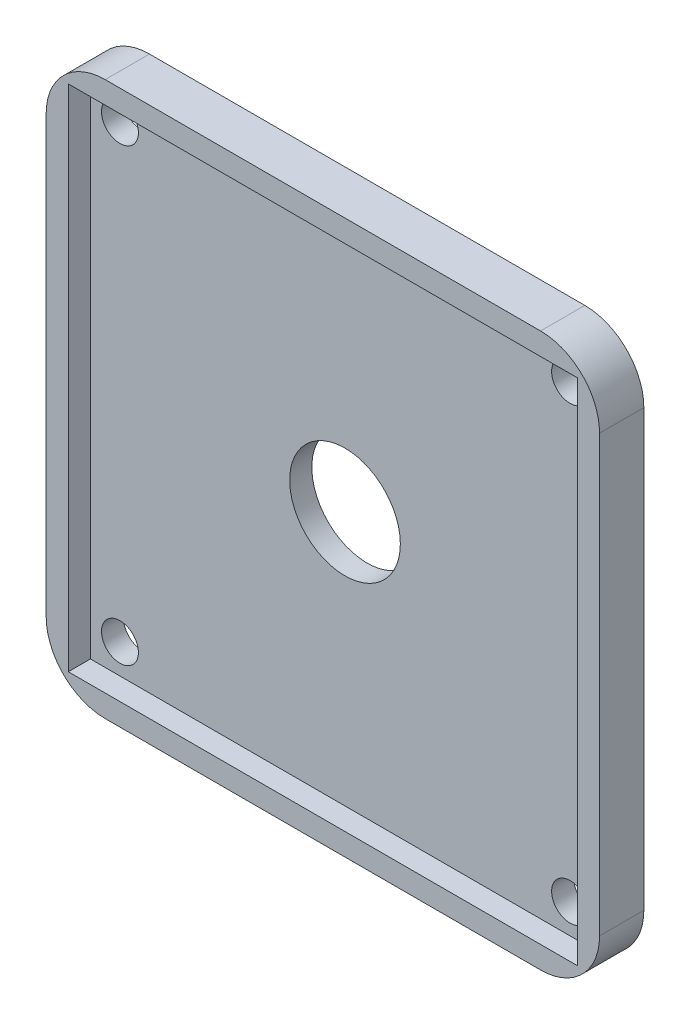
SolidWorks part; units mm, degrees
ref_plane "Front Plane" through (0, 0, 0) normal (0, 0, 1) x (1, 0, 0)
ref_plane "Top Plane" through (0, 0, 0) normal (0, 1, 0) x (1, 0, 0)
ref_plane "Right Plane" through (0, 0, 0) normal (1, 0, 0) x (0, 0, -1)
sketch "Sketch1" plane through (0, 0, 0) normal (0, 0, 1) x (1, 0, 0)
  line L0 (37.5, 75) -> (37.5, 0) construction
  line L1 (0, 0) -> (75, 0)
  line L2 (0, 0) -> (0, 75)
  line L3 (0, 75) -> (75, 75)
  line L4 (75, 0) -> (75, 75)
  line L5 (0, 37.5) -> (75, 37.5) construction
  line L6 (7, 75) -> (7, 68) construction
  line L7 (7, 68) -> (0, 68) construction
  circle A0 centre (7, 68) radius 2.5
  circle A1 centre (68, 68) radius 2.5
  circle A2 centre (68, 7) radius 2.5
  circle A3 centre (7, 7) radius 2.5
  circle A4 centre (37.5, 37.5) radius 7.5
  dimension "D2" = 5
  dimension "D4" = 15
  dimension "D1" = 75
  dimension "D3" = 7
extrude "Boss-Extrude1" add sketch "Sketch1" along normal blind 6
sketch "Sketch2" plane through (0, 0, 6) normal (0, 0, 1) x (1, 0, 0)
  line L0 (72, 3) -> (75, 3) construction
  line L1 (3, 72) -> (72, 72)
  line L2 (3, 72) -> (3, 3)
  line L3 (3, 3) -> (72, 3)
  line L4 (72, 72) -> (72, 3)
  line L5 (75, 0) -> (75, 75) construction
  line L6 (72, 3) -> (72, 0) construction
  line L7 (0, 0) -> (75, 0) construction
  line L8 (3, 72) -> (3, 75) construction
  line L9 (75, 75) -> (0, 75) construction
  line L10 (3, 72) -> (0, 72) construction
  line L11 (0, 75) -> (0, 0) construction
  dimension "D1" = 3
extrude "Cut-Extrude1" cut sketch "Sketch2" against normal blind 3
fillet "Fillet1" radius 8 4 edges at (0, 0, 3) (75, 0, 3) (75, 75, 3) (0, 75, 3)
